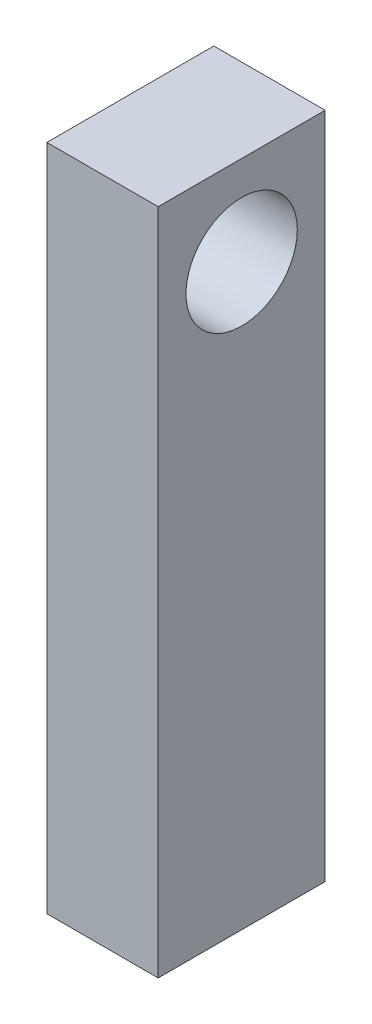
SolidWorks part; units mm, degrees
material "Aleación 1060"
ref_plane "Alzado" through (0, 0, 0) normal (0, 0, 1) x (1, 0, 0)
ref_plane "Planta" through (0, 0, 0) normal (0, 1, 0) x (1, 0, 0)
ref_plane "Vista lateral" through (0, 0, 0) normal (1, 0, 0) x (0, 0, -1)
sketch "Croquis1" plane through (0, 0, 0) normal (1, 0, 0) x (0, 0, -1)
  line L1 (-15, 60) -> (15, 60)
  line L2 (-15, 60) -> (-15, -60)
  line L3 (-15, -60) -> (15, -60)
  line L4 (15, 60) -> (15, -60)
  line L5 (-15, 60) -> (15, -60) construction
  line L6 (-15, -60) -> (15, 60) construction
  circle A0 centre (0, 43.9308) radius 10
  point P0 (0, 0)
  dimension "D3" = 20
  dimension "D1" = 120
  dimension "D2" = 30
extrude "Saliente-Extruir1" add sketch "Croquis1" along normal blind 20
